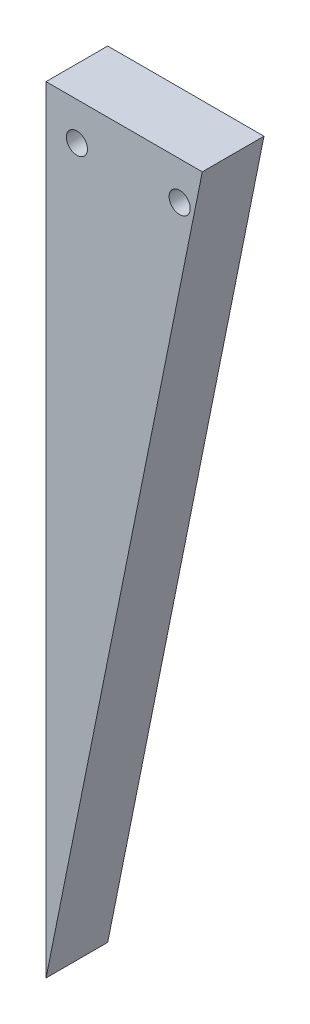
SolidWorks part; units mm, degrees
material "Acrylic (Medium-high impact)"
ref_plane "Front Plane" through (0, 0, 0) normal (0, 0, 1) x (1, 0, 0)
ref_plane "Top Plane" through (0, 0, 0) normal (0, 1, 0) x (1, 0, 0)
ref_plane "Right Plane" through (0, 0, 0) normal (1, 0, 0) x (0, 0, -1)
sketch "Sketch1" plane through (0, 0, 0) normal (0, 0, 1) x (1, 0, 0)
  line L0 (0, 0) -> (0, -119.888)
  line L1 (0, -55) -> (0, 55) construction
  line L2 (0, -119.888) -> (24.13, 0)
  line L3 (55, 0) -> (-55, 0) construction
  line L4 (24.13, 0) -> (0, 0)
  dimension "D1" = 119.888
  dimension "D2" = 24.13
extrude "Boss-Extrude1" add sketch "Sketch1" along normal blind 9.525
sketch "Sketch2" plane through (0, 0, 9.525) normal (0, 0, 1) x (1, 0, 0)
  line L0 (4.7625, -5.842) -> (20.6375, -5.842) construction
  line L1 (24.13, 0) -> (0, 0) construction
  line L2 (0, 0) -> (0, -119.888) construction
  dimension "D1" = 5.842
  dimension "D2" = 15.875
  dimension "D3" = 4.7625
hole_wizard "#4 Clearance Hole1" positions "Sketch4" profile "Sketch5" hole size "#4" standard "Ansi Inch" end condition through all
sketch "Sketch4" plane through (0, 0, 9.525) normal (0, 0, 1) x (1, 0, 0)
  point P1 (20.6375, -5.842)
  point P4 (4.7625, -5.842)
sketch "Sketch5" plane through (20.6375, -5.842, 9.525) normal (1, 0, 0) x (0, -1, 0)
  line L0 (0, 0) -> (0, 9.525)
  line L1 (0, 9.525) -> (1.6319, 9.525)
  line L2 (1.6319, 9.525) -> (1.6319, 0)
  line L5 (1.6319, 0) -> (0, 0)
  line L11 (0, -6.35) -> (0, 107.95) construction
  dimension "Thru Hole Dia." = 3.2639
  dimension "Thru Hole Depth" = 9.525
